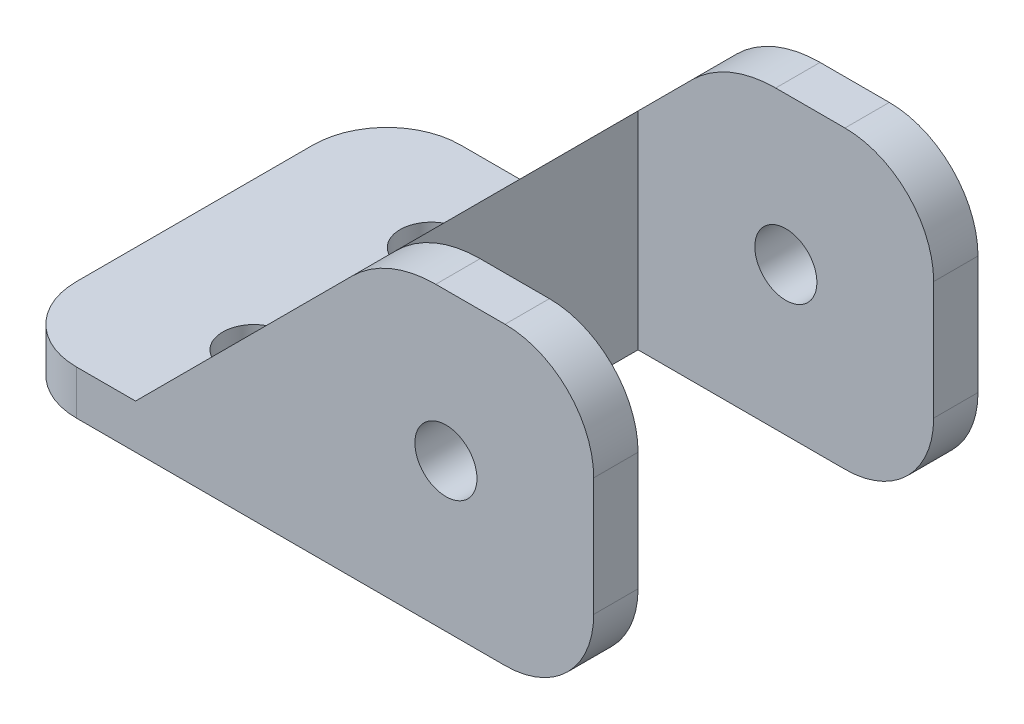
SolidWorks part; units mm, degrees
ref_plane "前视基准面" through (0, 0, 0) normal (0, 0, 1) x (1, 0, 0)
ref_plane "上视基准面" through (0, 0, 0) normal (0, 1, 0) x (1, 0, 0)
ref_plane "右视基准面" through (0, 0, 0) normal (1, 0, 0) x (0, 0, -1)
other "Configuration Table"
sketch "草图1" plane through (0, 0, 0) normal (0, 1, 0) x (1, 0, 0)
  line L1 (0, 0) -> (-15, 0)
  line L2 (0, 0) -> (0, 26)
  line L3 (0, 26) -> (-15, 26)
  line L4 (-20, 5) -> (-20, 21)
  arc A0 (-15, 0) -> (-20, 5) centre (-15, 5) cw
  arc A1 (-15, 26) -> (-20, 21) centre (-15, 21) ccw
  circle A2 centre (-10, 19) radius 2.1
  circle A3 centre (-10, 7) radius 2.1
  point P7 (-20, 0)
  point P10 (-20, 26)
  dimension "D3" = 5
  dimension "D4" = 4.2
  dimension "D7" = 4.2
  dimension "D1" = 26
  dimension "D2" = 20
  dimension "D5" = 7
  dimension "D6" = 7
  dimension "D8" = 10
  dimension "D9" = 10
extrude "凸台-拉伸1" add sketch "草图1" along normal blind 3
sketch "草图3" plane through (0, 0, 0) normal (0, 1, 0) x (1, 0, 0)
  line L0 (0, 26) -> (20, 26)
  line L1 (20, 26) -> (20, 23)
  line L2 (20, 23) -> (0, 23)
  line L3 (0, 0) -> (0, 26) construction
  line L4 (0, 23) -> (0, 26)
  line L5 (0, 0) -> (20, 0)
  line L6 (20, 0) -> (20, 3)
  line L7 (20, 3) -> (0, 3)
  line L8 (0, 3) -> (0, 0)
  dimension "D1" = 20
  dimension "D2" = 3
  dimension "D3" = 3
  dimension "D4" = 20
extrude "凸台-拉伸2" add sketch "草图3" along normal blind 20
fillet "圆角2" radius 6 4 edges at (20, 20, -1.5) (20, 0, -1.5) (20, 20, -24.5) (20, 0, -24.5)
chamfer "倒角2" distance 6 angle 45 2 edges at (0, 20, -1.5) (0, 20, -24.5)
fillet "圆角3" radius 8 2 edges at (6, 20, -1.5) (6, 20, -24.5)
sketch "草图8" plane through (0, 0, -26) normal (0, 0, -1) x (-1, 0, 0)
  line L0 (0, 14) -> (11, 3)
  line L1 (0, 3) -> (15, 3) construction
  line L2 (11, 3) -> (0, 3)
  line L3 (0, 3) -> (0, 14)
  dimension "D1" = 45
extrude "凸台-拉伸5" add sketch "草图8" against normal blind 26
sketch "草图12" plane through (0, 0, 0) normal (0, 0, 1) x (1, 0, 0)
  line L0 (20, 14) -> (20, 6) construction
  line L1 (14.3, 0) -> (-14.3, 0) construction
  circle A0 centre (10, 10) radius 2.1
  dimension "D1" = 4.2
  dimension "D2" = 10
  dimension "D3" = 10
extrude "切除-拉伸4" cut sketch "草图12" against normal blind 30
sketch "草图13" plane through (0, 3, 0) normal (0, 1, 0) x (1, 0, 0)
  circle A0 centre (-10, 19) radius 4
  circle A1 centre (-10, 7) radius 4
  dimension "D1" = 8
  dimension "D2" = 8
extrude "切除-拉伸5" cut sketch "草图13" along normal blind 30
